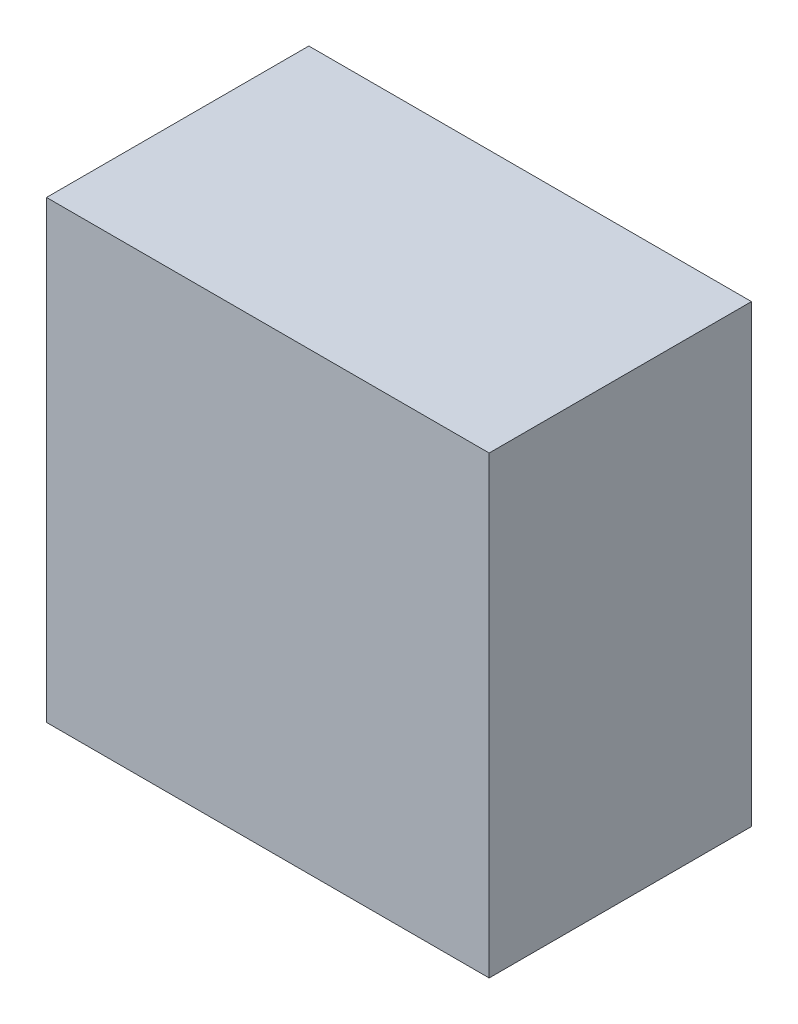
SolidWorks part; units mm, degrees
ref_plane "Front Plane" through (0, 0, 0) normal (0, 0, 1) x (1, 0, 0)
ref_plane "Top Plane" through (0, 0, 0) normal (0, 1, 0) x (1, 0, 0)
ref_plane "Right Plane" through (0, 0, 0) normal (1, 0, 0) x (0, 0, -1)
sketch "Sketch1" plane through (0, 0, 0) normal (0, 0, 1) x (1, 0, 0)
  line L0 (0, 0) -> (0, 26) construction
  line L1 (27.0353, 26) -> (-27.0353, 26) construction
  line L3 (12.6565, 0) -> (-12.6565, 0)
  line L4 (12.6565, 0) -> (12.6565, 26)
  line L5 (12.6565, 26) -> (-12.6565, 26)
  line L6 (-12.6565, 0) -> (-12.6565, 26)
  line L7 (12.6565, 0) -> (-12.6565, 26) construction
  line L8 (12.6565, 26) -> (-12.6565, 0) construction
  point P5 (0, 13)
extrude "Boss-Extrude1" add sketch "Sketch1" along normal blind 15
